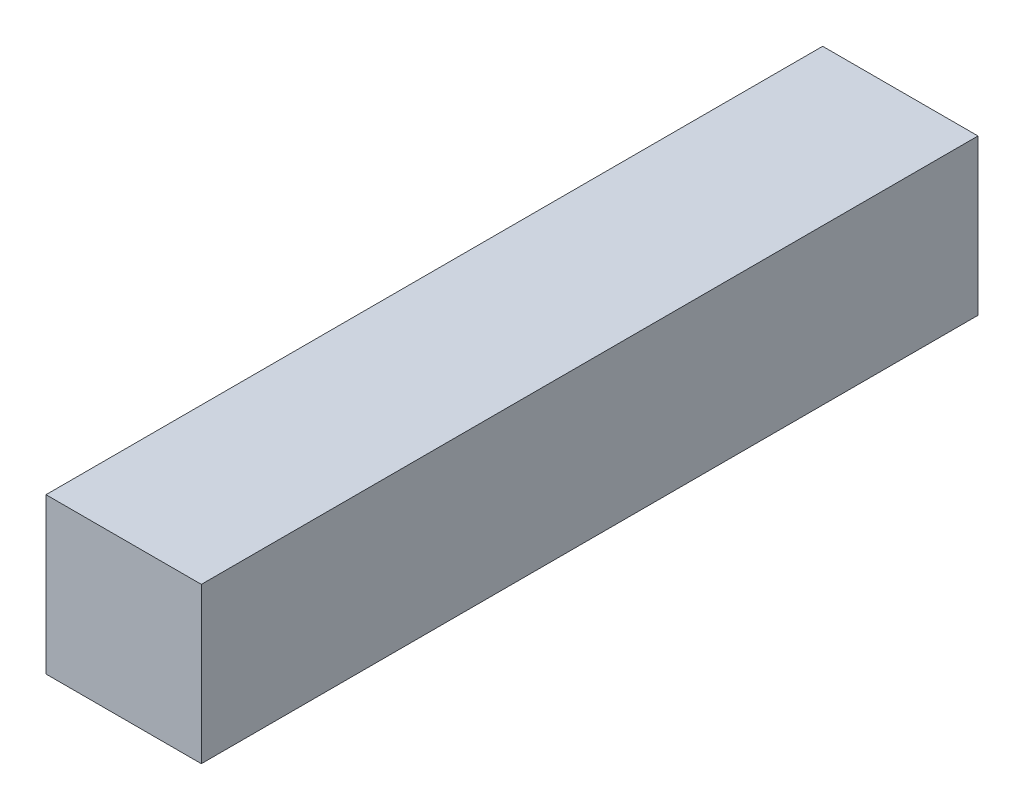
SolidWorks part; units mm, degrees
ref_plane "正面" through (0, 0, 0) normal (0, 0, 1) x (1, 0, 0)
ref_plane "平面"
ref_plane "右側面" through (0, 0, 0) normal (1, 0, 0) x (0, 0, -1)
sketch "ｽｹｯﾁ1" plane through (0, 0, 0) normal (0, 0, 1) x (1, 0, 0)
  line L1 (-1000, -1000) -> (1000, -1000)
  line L2 (-1000, -1000) -> (-1000, 1000)
  line L3 (-1000, 1000) -> (1000, 1000)
  line L4 (1000, -1000) -> (1000, 1000)
  line L5 (-1000, -1000) -> (1000, 1000) construction
  line L6 (-1000, 1000) -> (1000, -1000) construction
  point P0 (0, 0)
extrude "ﾎﾞｽ - 押し出し1" add sketch "ｽｹｯﾁ1" along normal blind 10000
